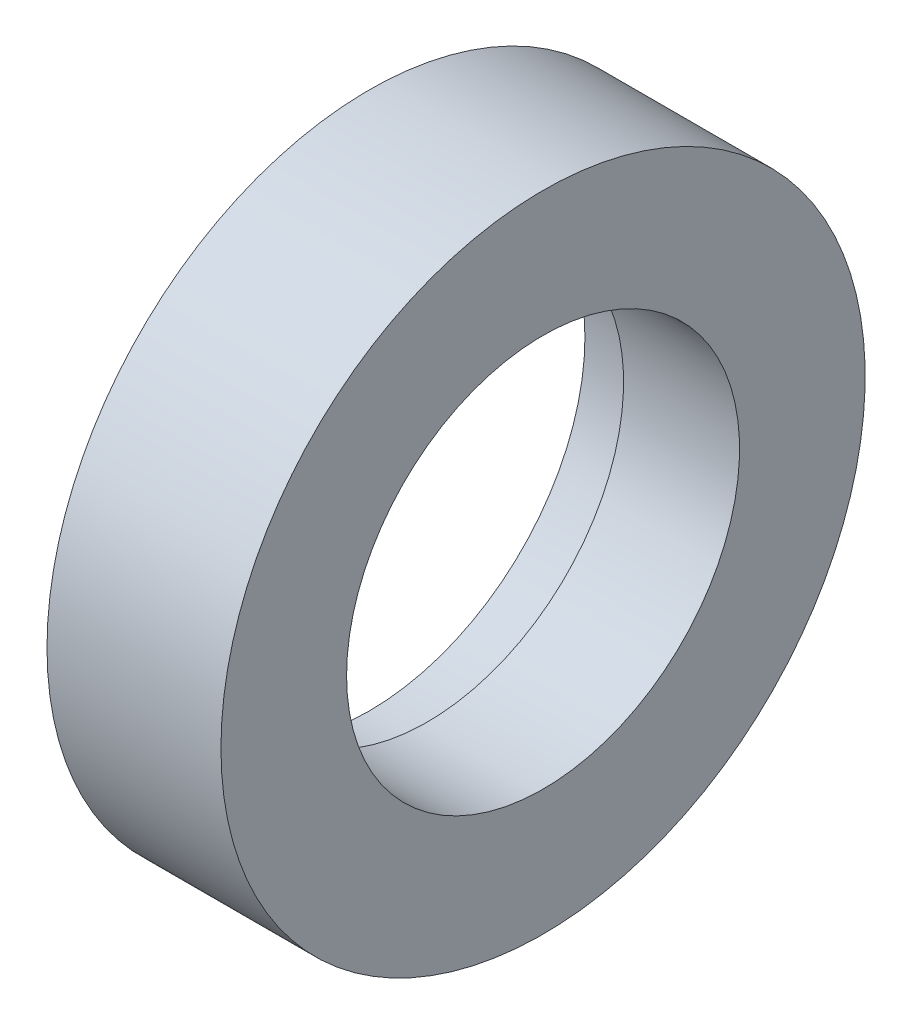
SolidWorks part; units mm, degrees
ref_plane "Front Plane" through (0, 0, 0) normal (0, 0, 1) x (1, 0, 0)
ref_plane "Top Plane" through (0, 0, 0) normal (0, 1, 0) x (1, 0, 0)
ref_plane "Right Plane" through (0, 0, 0) normal (1, 0, 0) x (0, 0, -1)
sketch "Sketch1" plane through (0, 0, 0) normal (0, 0, 1) x (1, 0, 0)
  line L0 (0, 0) -> (27.5576, 0) construction
  line L1 (0, 33.5) -> (9, 33.5)
  line L2 (9, 33.5) -> (9, 30.5)
  line L3 (9, 30.5) -> (27, 30.5)
  line L4 (27, 30.5) -> (27, 50)
  line L5 (27, 50) -> (0, 50)
  line L6 (0, 50) -> (0, 33.5)
  line L7 (0, 0) -> (0, 33.5) construction
  dimension "D1" = 27
  dimension "D2" = 61
  dimension "D3" = 67
  dimension "D4" = 100
  dimension "D5" = 18
revolve "Revolve1" add sketch "Sketch1" angle 360 about L0
